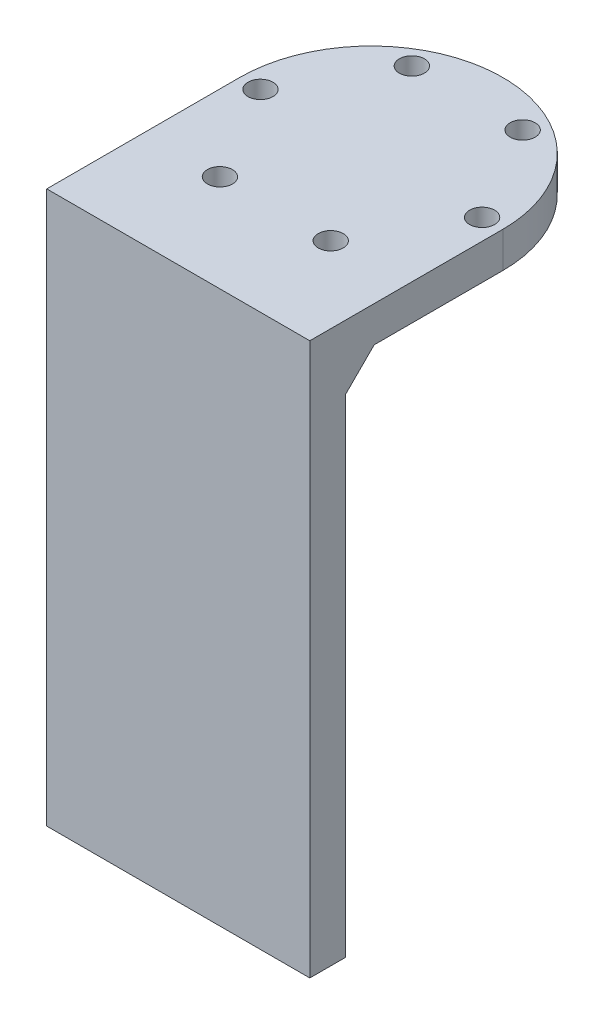
SolidWorks part; units mm, degrees
ref_plane "Płaszczyzna przednia" through (0, 0, 0) normal (0, 0, 1) x (1, 0, 0)
ref_plane "Płaszczyzna górna" through (0, 0, 0) normal (0, 1, 0) x (1, 0, 0)
ref_plane "Płaszczyzna prawa" through (0, 0, 0) normal (1, 0, 0) x (0, 0, -1)
sketch "Szkic2" plane through (0, 37.5292, 0) normal (0, -1, 0) x (1, 0, 0)
  line L0 (143.1444, 616.4067) -> (-26.8556, 616.4067) construction
  line L2 (76.5444, 616.4067) -> (39.7444, 616.4067)
  line L4 (39.7444, 589.4067) -> (39.7444, 616.4067)
  line L5 (76.5444, 589.4067) -> (76.5444, 616.4067)
  circle A0 centre (50.3944, 575.9833) radius 1.75 construction
  circle A1 centre (58.1444, 589.4067) radius 18.4
  arc A2 (39.7444, 589.4067) -> (76.5444, 589.4067) centre (58.1444, 589.4067) ccw
  circle A3 centre (65.8944, 575.9833) radius 1.75 construction
  circle A4 centre (73.6444, 589.4067) radius 1.75 construction
  circle A5 centre (65.8944, 602.8301) radius 1.75 construction
  circle A6 centre (50.3944, 602.8301) radius 1.75 construction
  circle A7 centre (42.6444, 589.4067) radius 1.75 construction
  circle A8 centre (50.3944, 575.9833) radius 1.75
  circle A9 centre (65.8944, 575.9833) radius 1.75
  circle A10 centre (73.6444, 589.4067) radius 1.75
  circle A11 centre (65.8944, 602.8301) radius 1.75
  circle A12 centre (50.3944, 602.8301) radius 1.75
  circle A13 centre (42.6444, 589.4067) radius 1.75
  dimension "D1" = 0
extrude "Dodanie-wyciągnięcie1" add sketch "Szkic2" along normal blind 5
sketch "Szkic3" plane through (0, 32.5292, 0) normal (0, -1, 0) x (1, 0, 0)
  line L0 (76.5444, 589.4067) -> (76.5444, 616.4067) construction
  line L1 (39.7444, 616.4067) -> (76.5444, 616.4067)
  line L2 (39.7444, 616.4067) -> (39.7444, 611.4067)
  line L3 (39.7444, 611.4067) -> (76.5444, 611.4067)
  line L4 (76.5444, 616.4067) -> (76.5444, 611.4067)
  line L5 (58.1444, 611.4067) -> (58.1444, 616.4067) construction
  line L6 (39.7444, 613.9067) -> (76.5444, 613.9067) construction
  point P132 (58.1444, 613.9067)
  dimension "D1" = 5
extrude "Dodanie-wyciągnięcie2" add sketch "Szkic3" along normal blind 72.2
chamfer "Sfazowanie1" distance 4 angle 45 1 edges at (58.1444, 32.5292, 611.4067)
